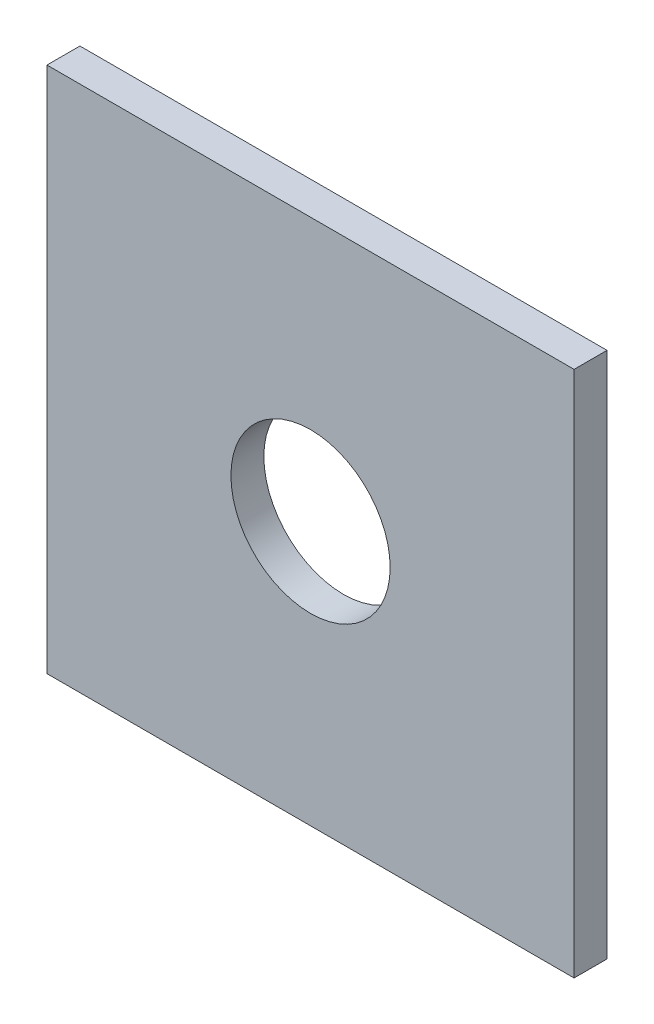
SolidWorks part; units mm, degrees
material "Mahogany"
ref_plane "Front Plane" through (0, 0, 0) normal (0, 0, 1) x (1, 0, 0)
ref_plane "Top Plane" through (0, 0, 0) normal (0, 1, 0) x (1, 0, 0)
ref_plane "Right Plane" through (0, 0, 0) normal (1, 0, 0) x (0, 0, -1)
sketch "Sketch1" plane through (0, 0, 0) normal (0, 0, 1) x (1, 0, 0)
  line L1 (152.4, 152.4) -> (-152.4, 152.4)
  line L2 (152.4, 152.4) -> (152.4, -152.4)
  line L3 (152.4, -152.4) -> (-152.4, -152.4)
  line L4 (-152.4, 152.4) -> (-152.4, -152.4)
  line L5 (152.4, 152.4) -> (-152.4, -152.4) construction
  line L6 (152.4, -152.4) -> (-152.4, 152.4) construction
  circle A0 centre (0, 0) radius 46.0375
  point P0 (0, 0)
  dimension "D3" = 92.075
  dimension "D1" = 304.8
  dimension "D2" = 304.8
extrude "Boss-Extrude1" add sketch "Sketch1" along normal blind 19.05
sketch "Sketch2" plane through (0, 0, 0) normal (0, 0, 1) x (1, 0, 0)
  line L0 (-71.842, 71.842) -> (0, 0) construction
  line L1 (0, 0) -> (71.842, -71.842) construction
  line L2 (0, 0) -> (152.4, 0) construction
  line L3 (152.4, -152.4) -> (152.4, 152.4) construction
  circle A0 centre (-71.842, 71.842) radius 7.9375
  circle A1 centre (71.842, -71.842) radius 7.9375
  dimension "D2" = 15.875
  dimension "D3" = 15.875
  dimension "D1" = 101.6
  dimension "D4" = 45
extrude "Cut-Extrude1" cut sketch "Sketch2" along normal offset from surface (15.875 mm away) 3.175 up to face at (0, 0, 19.05)
